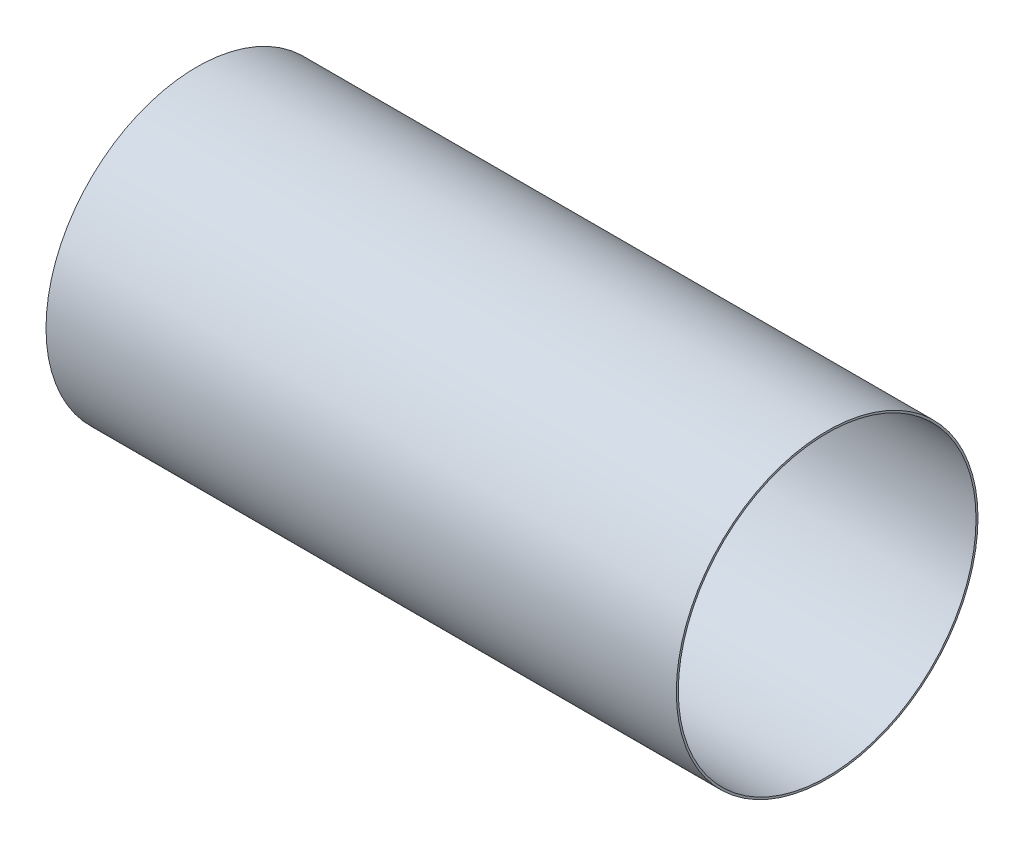
SolidWorks part; units mm, degrees
ref_plane "Front Plane" through (0, 0, 0) normal (0, 0, 1) x (1, 0, 0)
ref_plane "Top Plane" through (0, 0, 0) normal (0, 1, 0) x (1, 0, 0)
ref_plane "Right Plane" through (0, 0, 0) normal (1, 0, 0) x (0, 0, -1)
sketch "Sketch1" plane through (0, 0, 0) normal (1, 0, 0) x (0, 0, -1)
  circle A0 centre (0, 0) radius 75
  circle A1 centre (0, 0) radius 76
  dimension "D1" = 150
  dimension "D2" = 1
extrude "Boss-Extrude1" add sketch "Sketch1" along normal blind 317.6
